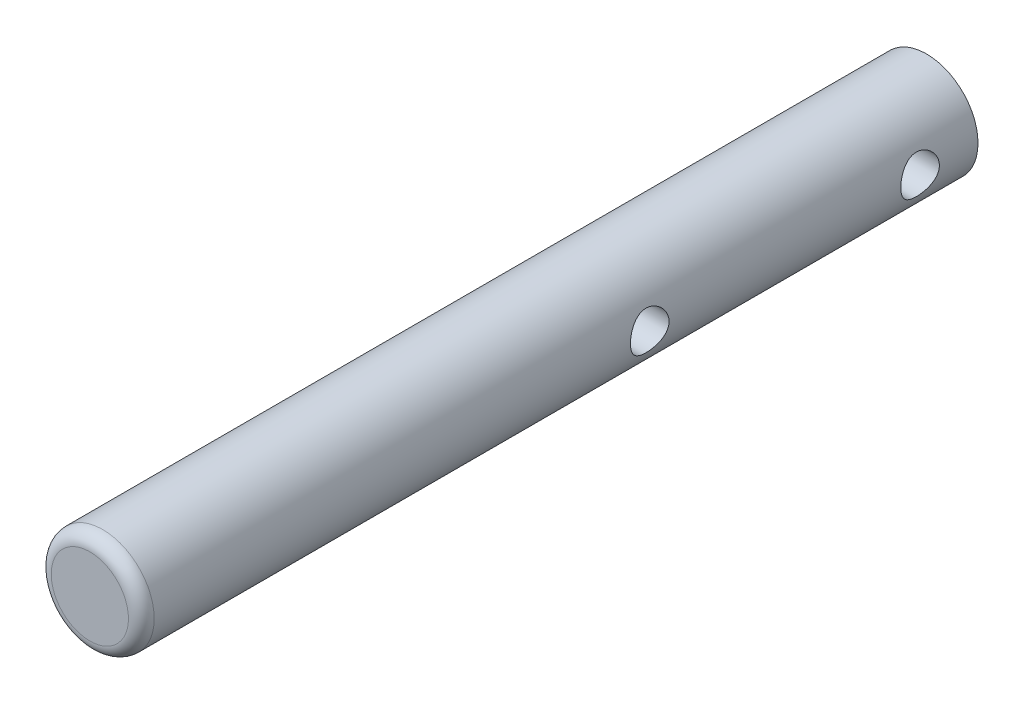
SolidWorks part; units mm, degrees
material "Alliage 1060"
ref_plane "Plan de face" through (0, 0, 0) normal (0, 0, 1) x (1, 0, 0)
ref_plane "Plan de dessus" through (0, 0, 0) normal (0, 1, 0) x (1, 0, 0)
ref_plane "Plan de droite" through (0, 0, 0) normal (1, 0, 0) x (0, 0, -1)
sketch "Esquisse1" plane through (0, 0, 0) normal (0, 0, 1) x (1, 0, 0)
  circle A0 centre (0, 0) radius 4
  dimension "D1" = 8
extrude "Boss.-Extru.1" add sketch "Esquisse1" along normal blind 65
sketch "Esquisse2" plane through (0, 0, 0) normal (1, 0, 0) x (0, 0, -1)
  circle A0 centre (-25.5, 0) radius 1.5
  circle A1 centre (-4.5, 0) radius 1.5
  dimension "D1" = 4.5
  dimension "D2" = 21
  dimension "D3" = 3
extrude "Enlèv. mat.-Extru.1" cut sketch "Esquisse2" against normal mid plane 10
fillet "Congé1" radius 1 1 edges at (4, 0, 65)
